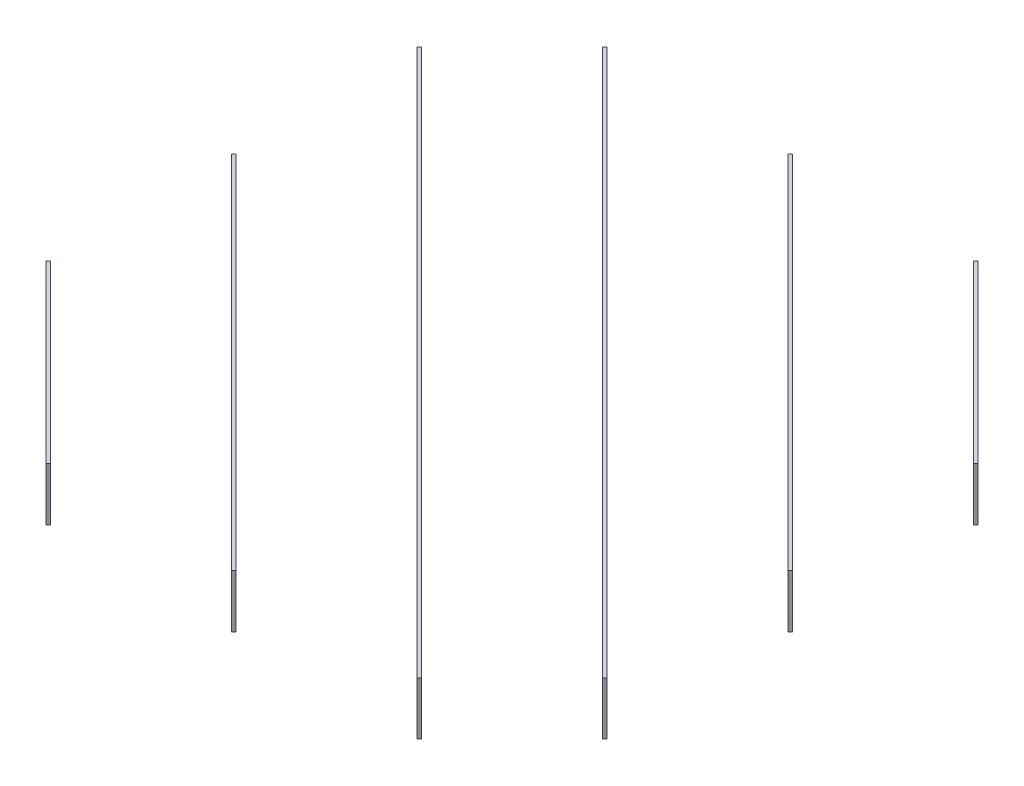
SolidWorks part; units mm, degrees
material "Plain Carbon Steel"
ref_plane "Front" through (0, 0, 0) normal (0, 0, 1) x (1, 0, 0)
ref_plane "Top" through (0, 0, 0) normal (0, 1, 0) x (1, 0, 0)
ref_plane "Right" through (0, 0, 0) normal (1, 0, 0) x (0, 0, -1)
sketch "Sketch1" plane through (0, 0, 0) normal (0, 1, 0) x (1, 0, 0)
  line L0 (-525, -525) -> (-525, 525) construction
  line L1 (-605, 605) -> (605, 605) construction
  line L2 (-605, 605) -> (-605, -605) construction
  line L3 (-605, -605) -> (605, -605) construction
  line L4 (605, 605) -> (605, -605) construction
  line L5 (-605, 605) -> (605, -605) construction
  line L6 (-605, -605) -> (605, 605) construction
  line L7 (-525, 525) -> (525, 525) construction
  line L8 (-525, 350) -> (525, 350) construction
  line L9 (-525, 175) -> (525, 175) construction
  line L10 (-525, 0) -> (525, 0) construction
  line L11 (-525, -175) -> (525, -175) construction
  line L12 (-525, -350) -> (525, -350) construction
  line L13 (-525, -525) -> (525, -525) construction
  line L14 (-350, -525) -> (-350, 525) construction
  line L15 (-175, -525) -> (-175, 525) construction
  line L16 (0, -525) -> (0, 525) construction
  line L17 (175, -525) -> (175, 525) construction
  line L18 (350, -525) -> (350, 525) construction
  line L19 (525, -525) -> (525, 525) construction
  point P0 (0, 0)
  dimension "D1" = 1210
  dimension "D2" = 1210
  dimension "D5" = 175
  dimension "D3" = 7
  dimension "D4" = 7
sketch "Sketch2" plane through (0, 0, 0) normal (0, 1, 0) x (1, 0, 0)
  line L0 (-605, -274.2426) -> (-274.2426, -605)
  line L1 (-602.8787, 602.8787) -> (602.8787, 602.8787) construction
  line L2 (-602.8787, 602.8787) -> (-602.8787, -602.8787) construction
  line L3 (-602.8787, -602.8787) -> (602.8787, -602.8787) construction
  line L4 (602.8787, 602.8787) -> (602.8787, -602.8787) construction
  line L5 (-602.8787, 602.8787) -> (602.8787, -602.8787) construction
  line L6 (-602.8787, -602.8787) -> (602.8787, 602.8787) construction
  line L7 (-605, 605) -> (605, -605) construction
  line L8 (-427.8787, 602.8787) -> (602.8787, -427.8787) construction
  line L9 (-77.8787, 602.8787) -> (602.8787, -77.8787) construction
  line L10 (272.1213, 602.8787) -> (602.8787, 272.1213) construction
  line L11 (-602.8787, -272.1213) -> (-272.1213, -602.8787) construction
  line L12 (-602.8787, 77.8787) -> (77.8787, -602.8787) construction
  line L13 (-602.8787, 427.8787) -> (427.8787, -602.8787) construction
  line L14 (-605, 75.7574) -> (75.7574, -605)
  line L15 (-605, 425.7574) -> (425.7574, -605)
  line L16 (-430, 600.7574) -> (600.7574, -430)
  line L17 (-80, 600.7574) -> (600.7574, -80)
  line L18 (270, 600.7574) -> (600.7574, 270)
  line L19 (-600.7574, -270) -> (-270, -600.7574)
  line L20 (-600.7574, 80) -> (80, -600.7574)
  line L21 (-600.7574, 430) -> (430, -600.7574)
  line L22 (-425.7574, 605) -> (605, -425.7574)
  line L23 (-75.7574, 605) -> (605, -75.7574)
  line L24 (274.2426, 605) -> (605, 274.2426)
  line L25 (-605, -274.2426) -> (-600.7574, -270)
  line L26 (-274.2426, -605) -> (-270, -600.7574)
  line L27 (-605, 75.7574) -> (-600.7574, 80)
  line L28 (75.7574, -605) -> (80, -600.7574)
  line L29 (-605, 425.7574) -> (-600.7574, 430)
  line L30 (425.7574, -605) -> (430, -600.7574)
  line L31 (-430, 600.7574) -> (-425.7574, 605)
  line L32 (600.7574, -430) -> (605, -425.7574)
  line L33 (-80, 600.7574) -> (-75.7574, 605)
  line L34 (600.7574, -80) -> (605, -75.7574)
  line L35 (270, 600.7574) -> (274.2426, 605)
  line L36 (600.7574, 270) -> (605, 274.2426)
  line L38 (-605, 605) -> (605, 605) construction
  line L39 (605, 605) -> (605, -605) construction
extrude "Boss-Extrude1" add sketch "Sketch2" along normal blind 100
sketch "Sketch3" plane through (-439.6213, 0, 439.6213) normal (-0.7071, 0, 0.7071) x (0.7071, 0, 0.7071)
  line L0 (-742.4621, 0) -> (0, 0) construction
  line L1 (-126.7056, 50) -> (-120.7056, 50)
  line L2 (-126.7056, 50) -> (-126.7056, -50)
  line L3 (-126.7056, -50) -> (-120.7056, -50)
  line L4 (-120.7056, 50) -> (-120.7056, -50)
  line L5 (-126.7056, 50) -> (-120.7056, -50) construction
  line L6 (-126.7056, -50) -> (-120.7056, 50) construction
  line L7 (123.7437, 0) -> (-618.7184, 0) construction
  line L8 (-374.2311, 50) -> (-368.2311, 50)
  line L9 (-374.2311, 50) -> (-374.2311, -50)
  line L10 (-374.2311, -50) -> (-368.2311, -50)
  line L11 (-368.2311, 50) -> (-368.2311, -50)
  line L12 (-374.2311, 50) -> (-368.2311, -50) construction
  line L13 (-374.2311, -50) -> (-368.2311, 50) construction
  line L14 (-621.7184, 50) -> (-615.7184, 50)
  line L15 (-621.7184, 50) -> (-621.7184, -50)
  line L16 (-621.7184, -50) -> (-615.7184, -50)
  line L17 (-615.7184, 50) -> (-615.7184, -50)
  line L18 (-621.7184, 50) -> (-615.7184, -50) construction
  line L19 (-621.7184, -50) -> (-615.7184, 50) construction
  line L20 (0, 0) -> (0, 100) construction
  line L21 (-233.8808, 100) -> (233.8808, 100) construction
  line L22 (621.7184, -50) -> (615.7184, 50) construction
  line L23 (621.7184, 50) -> (615.7184, -50) construction
  line L24 (374.2311, -50) -> (368.2311, 50) construction
  line L25 (374.2311, 50) -> (368.2311, -50) construction
  line L26 (126.7056, -50) -> (120.7056, 50) construction
  line L27 (126.7056, 50) -> (120.7056, -50) construction
  line L28 (615.7184, 50) -> (615.7184, -50)
  line L29 (621.7184, -50) -> (615.7184, -50)
  line L30 (621.7184, 50) -> (621.7184, -50)
  line L31 (621.7184, 50) -> (615.7184, 50)
  line L32 (368.2311, 50) -> (368.2311, -50)
  line L33 (374.2311, -50) -> (368.2311, -50)
  line L34 (374.2311, 50) -> (374.2311, -50)
  line L35 (374.2311, 50) -> (368.2311, 50)
  line L36 (120.7056, 50) -> (120.7056, -50)
  line L37 (126.7056, -50) -> (120.7056, -50)
  line L38 (126.7056, 50) -> (126.7056, -50)
  line L39 (126.7056, 50) -> (120.7056, 50)
  circle A0 centre (-126.7056, 50) radius 1.5
  circle A1 centre (-120.7056, 50) radius 1.5
  circle A2 centre (-621.7184, 50) radius 1.5
  circle A3 centre (-615.7184, 50) radius 1.5
  circle A4 centre (-374.2311, 50) radius 1.5
  circle A5 centre (-368.2311, 50) radius 1.5
  circle A6 centre (368.2311, 50) radius 1.5
  circle A7 centre (374.2311, 50) radius 1.5
  circle A8 centre (615.7184, 50) radius 1.5
  circle A9 centre (621.7184, 50) radius 1.5
  circle A10 centre (120.7056, 50) radius 1.5
  circle A11 centre (126.7056, 50) radius 1.5
  point P0 (-123.7056, 0)
  point P7 (-371.2311, 0)
  point P12 (-618.7184, 0)
  point P48 (618.7184, 0)
  point P49 (371.2311, 0)
  point P50 (123.7056, 0)
  line M15 (-233.8808, 0) -> (233.8808, 0)
  dimension "D1" = 100
  dimension "D7" = 3
  dimension "D8" = 3
  dimension "D9" = 3
  dimension "D10" = 3
  dimension "D11" = 3
  dimension "D12" = 3
  dimension "D2" = 100
  dimension "D3" = 100
  dimension "D4" = 3
  dimension "D5" = 3
  dimension "D6" = 3
extrude "Cut-Extrude1" cut sketch "Sketch3" against normal through all contours A3 L14 A2 L15 L16 L17 | L14 A2 L15 | L17 A3 L14 | L14 A3 L17 | L15 A2 L14 | L8 A4 L9 | L9 A4 L8 | A5 L8 A4 L9 L10 L11 | L8 A5 L11 | L11 A5 L8 | L1 A0 L2 | L4 A1 L1 | L1 A1 L4 | A1 L1 A0 L2 L4 M15 | L2 A0 L1 | A10 L36 L39 | A10 L39 L36 | L38 A11 L39 A10 L36 M15 | A11 L38 L39 | A11 L39 L38 | A6 L32 L35 | L34 A7 L35 A6 L32 L33 | A7 L35 L34 | A7 L34 L35 | A6 L35 L32 | A8 L28 L31 | A9 L31 L30 | L30 A9 L31 A8 L28 L29 | A9 L30 L31 | A8 L31 L28
sketch "Sketch6" plane through (260.3787, 0, -260.3787) normal (-0.7071, 0, 0.7071) x (0.7071, 0, 0.7071)
  line L0 (-0.0191, 81) -> (-0.0191, 75) construction
  line L1 (14.9809, 81) -> (-15.0191, 81) construction
  line L2 (-15.0191, 75) -> (14.9809, 75) construction
  line L3 (24.9809, 75) -> (24.9809, 81) construction
  line L4 (-28.0191, 84) -> (27.9809, 84)
  line L5 (-28.0191, 84) -> (-28.0191, 72)
  line L6 (-28.0191, 72) -> (27.9809, 72)
  line L7 (27.9809, 84) -> (27.9809, 72)
  line L8 (-28.0191, 84) -> (27.9809, 72) construction
  line L9 (-28.0191, 72) -> (27.9809, 84) construction
  point P6 (-0.0191, 78)
  dimension "D1" = 3
  dimension "D2" = 3
extrude "Cut-Extrude3" cut sketch "Sketch6" against normal up to next (6 mm away)
sketch "Sketch7" plane through (-264.6213, 0, 264.6213) normal (-0.7071, 0, 0.7071) x (0.7071, 0, 0.7071)
  line L4 (27.9809, 84) -> (-28.0191, 84)
  line L5 (27.9809, 72) -> (27.9809, 84)
  line L6 (-28.0191, 72) -> (27.9809, 72)
  line L7 (-28.0191, 84) -> (-28.0191, 72)
  line L8 (27.9809, 84) -> (-28.0191, 84)
  line L9 (27.9809, 72) -> (27.9809, 84)
  line L10 (-28.0191, 72) -> (27.9809, 72)
  line L11 (-28.0191, 84) -> (-28.0191, 72)
  dimension "D1" = 0
extrude "Cut-Extrude4" cut sketch "Sketch7" against normal up to next (6 mm away)
equation "\"Plate width\"= 100mm"
equation "\"D1@Boss-Extrude1\"=\"Plate width\""
equation "\"D1@Sketch3\"=\"Plate width\""
equation "\"D2@Sketch3\"=\"Plate width\""
equation "\"D3@Sketch3\"=\"Plate width\""
equation "\"D4@Sketch3\"=\"half plate thickness\""
equation "\"D5@Sketch3\"=\"half plate thickness\""
equation "\"D6@Sketch3\"=\"half plate thickness\""
equation "\"D7@Sketch3\"=\"half plate thickness\""
equation "\"D8@Sketch3\"=\"half plate thickness\""
equation "\"D9@Sketch3\"=\"half plate thickness\""
equation "\"D10@Sketch3\"=\"half plate thickness\""
equation "\"D11@Sketch3\"=\"half plate thickness\""
equation "\"D12@Sketch3\"=\"half plate thickness\""
